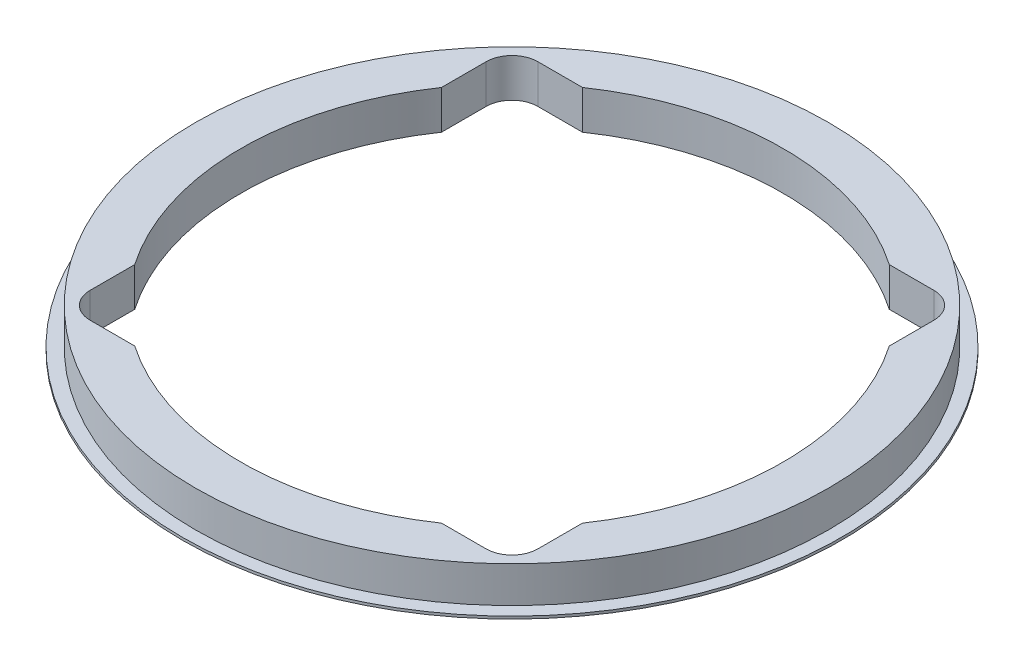
SolidWorks part; units mm, degrees
ref_plane "前视基准面" through (0, 0, 0) normal (0, 0, 1) x (1, 0, 0)
ref_plane "上视基准面" through (0, 0, 0) normal (0, 1, 0) x (1, 0, 0)
ref_plane "右视基准面" through (0, 0, 0) normal (1, 0, 0) x (0, 0, -1)
other "Configuration Table"
sketch "草图1" plane through (0, 0, 0) normal (0, 1, 0) x (1, 0, 0)
  circle A0 centre (0, 0) radius 24.5
  circle A1 centre (0, 0) radius 21
  dimension "D1" = 42
  dimension "D2" = 49
extrude "凸台-拉伸1" add sketch "草图1" along normal blind 3
sketch "草图2" plane through (0, 0, 0) normal (0, -1, 0) x (1, 0, 0)
  circle A0 centre (0, 0) radius 24.5
  circle A1 centre (0, 0) radius 25.5
  circle A2 centre (0, 0) radius 24.5 construction
  dimension "D1" = 1
extrude "凸台-拉伸2" add sketch "草图2" against normal blind 0.2
sketch "草图3" plane through (0, 3, 0) normal (0, 1, 0) x (1, 0, 0)
  line L1 (-15.3241, 17.3241) -> (15.3241, 17.3241)
  line L2 (-17.3241, 15.3241) -> (-17.3241, -15.3241)
  line L3 (-15.3241, -17.3241) -> (15.3241, -17.3241)
  line L4 (17.3241, 15.3241) -> (17.3241, -15.3241)
  circle A0 centre (0, 0) radius 24.5 construction
  circle A1 centre (0, 0) radius 24.5 construction
  arc A2 (15.3241, -17.3241) -> (17.3241, -15.3241) centre (15.3241, -15.3241) ccw
  arc A3 (17.3241, 15.3241) -> (15.3241, 17.3241) centre (15.3241, 15.3241) ccw
  arc A4 (-17.3241, 15.3241) -> (-15.3241, 17.3241) centre (-15.3241, 15.3241) cw
  arc A5 (-15.3241, -17.3241) -> (-17.3241, -15.3241) centre (-15.3241, -15.3241) cw
  point P4 (-16.4968, 18.7845)
  point P7 (17.5869, 17.768)
  point P8 (-17.1508, -18.1893)
  point P15 (17.3241, 17.3241)
  point P18 (-17.3241, 17.3241)
  point P21 (-17.3241, -17.3241)
  dimension "D1" = 2
extrude "切除-拉伸3" cut sketch "草图3" against normal up to next and the other way through all
